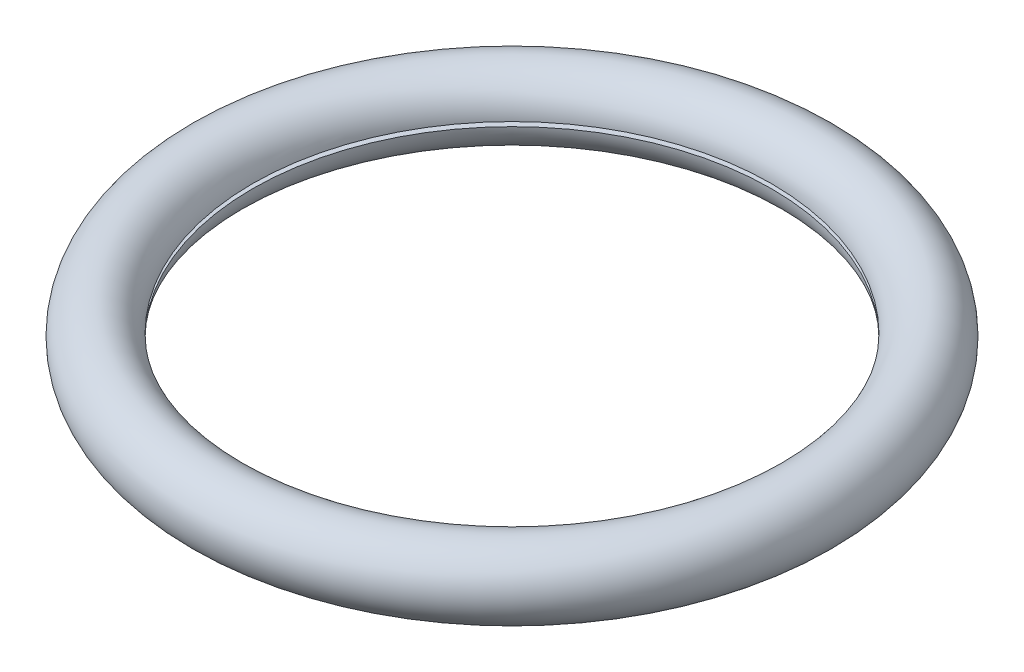
SolidWorks part; units mm, degrees
ref_plane "Front Plane" through (0, 0, 0) normal (0, 0, 1) x (1, 0, 0)
ref_plane "Top Plane" through (0, 0, 0) normal (0, 1, 0) x (1, 0, 0)
ref_plane "Right Plane" through (0, 0, 0) normal (1, 0, 0) x (0, 0, -1)
sketch "Sketch1" plane through (0, 0, 0) normal (0, 0, 1) x (1, 0, 0)
  line L1 (0, 65.6718) -> (0, -31.335) construction
  line L2 (164.4663, -2.3766) -> (150.4077, -2.3766)
  line L4 (164.4663, -4.9166) -> (150.4077, -4.9166)
  arc A2 (164.4663, -4.9166) -> (164.4663, -2.3766) centre (170.688, -3.6466) ccw
  arc A3 (150.4077, -4.9166) -> (150.4077, -2.3766) centre (170.688, -3.6466) ccw
  point P0 (177.038, -3.6466)
  dimension "D1" = 1.27
  dimension "D2" = 1.27
  dimension "D3" = 12.7
  dimension "D4" = 40.64
  dimension "D5" = 177.038
revolve "Revolve2" add sketch "Sketch1" angle 360 about L1
